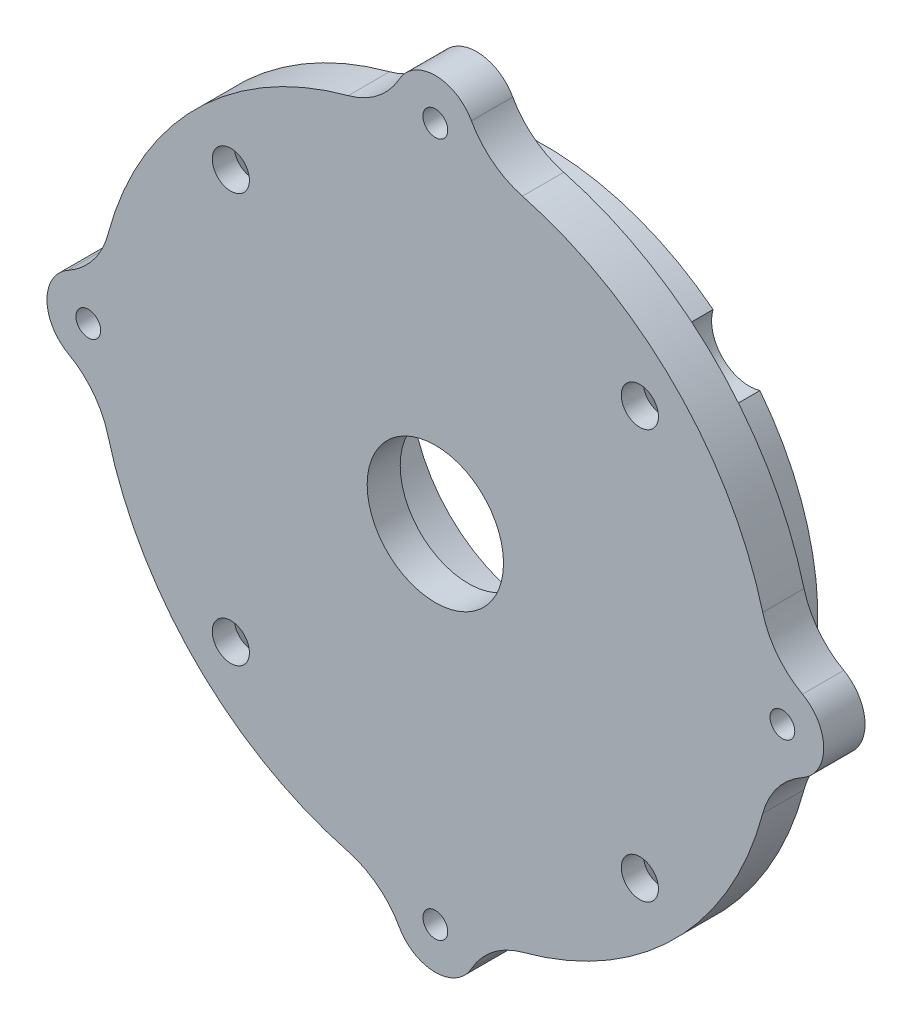
SolidWorks part; units mm, degrees
ref_plane "Ön Düzlem" through (0, 0, 0) normal (0, 0, 1) x (1, 0, 0)
ref_plane "Üst Düzlem" through (0, 0, 0) normal (0, 1, 0) x (1, 0, 0)
ref_plane "Sağ Düzlem" through (0, 0, 0) normal (1, 0, 0) x (0, 0, -1)
sketch "Çizim1" plane through (0, 0, 0) normal (0, 0, 1) x (1, 0, 0)
  circle A0 centre (0, 0) radius 16.25
  circle A1 centre (0, 0) radius 22.5
  circle A2 centre (0, 0) radius 33.05
  circle A3 centre (0, 0) radius 28
  dimension "D1" = 32.5
  dimension "D2" = 45
  dimension "D3" = 66.1
  dimension "D4" = 56
extrude "Yükseklik-Ekstrüzyon1" add sketch "Çizim1" along normal blind 8.25 contours A1 A0 | A2 A3
sketch "Çizim2" plane through (0, 0, 8.25) normal (0, 0, 1) x (1, 0, 0)
  circle A0 centre (-24.75, 24.75) radius 2
  circle A1 centre (24.75, 24.75) radius 2
  circle A2 centre (24.75, -24.75) radius 2
  circle A3 centre (-24.75, -24.75) radius 2
  arc A6 (-10.5408, 39.6218) -> (-39.6218, 10.5408) centre (0, 0) ccw
  circle A7 centre (0, 42) radius 1.5
  arc A8 (4.3706, 44.4286) -> (-4.3706, 44.4286) centre (0, 42) ccw
  arc A9 (-4.3706, 44.4286) -> (-10.5408, 39.6218) centre (-13.1118, 49.2857) cw
  arc A10 (4.3706, 44.4286) -> (10.5408, 39.6218) centre (13.1118, 49.2857) ccw
  arc A11 (44.4286, 4.3706) -> (39.6218, 10.5408) centre (49.2857, 13.1118) cw
  arc A12 (44.4286, -4.3706) -> (44.4286, 4.3706) centre (42, 0) ccw
  circle A13 centre (42, 0) radius 1.5
  arc A14 (44.4286, -4.3706) -> (39.6218, -10.5408) centre (49.2857, -13.1118) ccw
  arc A15 (4.3706, -44.4286) -> (10.5408, -39.6218) centre (13.1118, -49.2857) cw
  arc A16 (-4.3706, -44.4286) -> (4.3706, -44.4286) centre (0, -42) ccw
  circle A17 centre (0, -42) radius 1.5
  arc A18 (-4.3706, -44.4286) -> (-10.5408, -39.6218) centre (-13.1118, -49.2857) ccw
  arc A19 (-44.4286, -4.3706) -> (-39.6218, -10.5408) centre (-49.2857, -13.1118) cw
  arc A20 (-44.4286, 4.3706) -> (-44.4286, -4.3706) centre (-42, 0) ccw
  circle A21 centre (-42, 0) radius 1.5
  arc A22 (-44.4286, 4.3706) -> (-39.6218, 10.5408) centre (-49.2857, 13.1118) ccw
  arc A23 (-39.6218, -10.5408) -> (-10.5408, -39.6218) centre (0, 0) ccw
  arc A24 (10.5408, -39.6218) -> (39.6218, -10.5408) centre (0, 0) ccw
  arc A25 (39.6218, 10.5408) -> (10.5408, 39.6218) centre (0, 0) ccw
  circle A26 centre (0, 0) radius 8.25
  point P0 (0, 0)
  point P17 (0, 0)
  point P48 (0, 0)
  dimension "D3" = 4
  dimension "D4" = 24.75
  dimension "D5" = 24.75
  dimension "D1" = 82
  dimension "D2" = 42
  dimension "D7" = 10
  dimension "D8" = 3
  dimension "D9" = 10
  dimension "D10" = 10
  dimension "D12" = 16.5
  dimension "D6" = 4
  dimension "D11" = 4
extrude "Yükseklik-Ekstrüzyon2" add sketch "Çizim2" along normal blind 5
hole_wizard "M4 Altıgen Alyan Havşa Başlı Vida İçin Havşa2" positions "3B Çizim1" profile "Çizim5" countersink size "M4" standard "DIN"
sketch3d "3B Çizim1"
  line L0 (24.75, 24.75, 13.25) -> (24.75, 24.75, 8.25) construction
  line L1 (-24.75, 24.75, 13.25) -> (-24.75, 24.75, 8.25) construction
  line L2 (-24.75, -24.75, 13.25) -> (-24.75, -24.75, 8.25) construction
  line L3 (24.75, -24.75, 13.25) -> (24.75, -24.75, 8.25) construction
  point P0 (24.75, 24.75, 8.25)
  point P4 (-24.75, 24.75, 8.25)
  point P8 (-24.75, -24.75, 8.25)
  point P12 (24.75, -24.75, 8.25)
sketch "Çizim5" plane through (24.75, 24.75, 8.25) normal (1, 0, 0) x (0, 1, 0)
  line L0 (0, 0) -> (0, 5)
  line L1 (0, 5) -> (2.25, 5)
  line L2 (2.25, 5) -> (2.25, 2.34)
  line L3 (2.25, 2.34) -> (4.59, 0)
  line L5 (4.59, 0) -> (0, 0)
  line L6 (-2.25, 2.34) -> (-4.59, 0) construction
  line L11 (0, -6.35) -> (0, 107.95) construction
  dimension "Thru Hole Dia." = 4.5
  dimension "Thru Hole Depth" = 5
  dimension "Near C'Sink Dia." = 9.18
  dimension "Near C'Sink Angle" = 90
sketch "Çizim7" plane through (0, 0, 8.25) normal (0, 0, -1) x (-1, 0, 0)
  circle A0 centre (0, 0) radius 16.25 construction
  circle A1 centre (0, 0) radius 16.25
extrude "Kes-Ekstrüzyon2" cut sketch "Çizim7" against normal blind 1
sketch "Çizim8" plane through (0, 0, 0) normal (0, 0, -1) x (-1, 0, 0)
  circle A0 centre (-24.75, 24.75) radius 4.5672
  circle A1 centre (24.75, 24.75) radius 4.5672
  circle A2 centre (24.75, -24.75) radius 4.5672
  circle A3 centre (-24.75, -24.75) radius 4.5672
  point P3 (47.0428, 34.5959)
  point P4 (0, 0)
  point P5 (0, 0)
  point P12 (0, 0)
  point P15 (0, 0)
  dimension "D2" = 9.1344
  dimension "D1" = 4
extrude "Kes-Ekstrüzyon3" cut sketch "Çizim8" against normal up to surface (8.25 mm away) up to face at (0, 0, 8.25)
